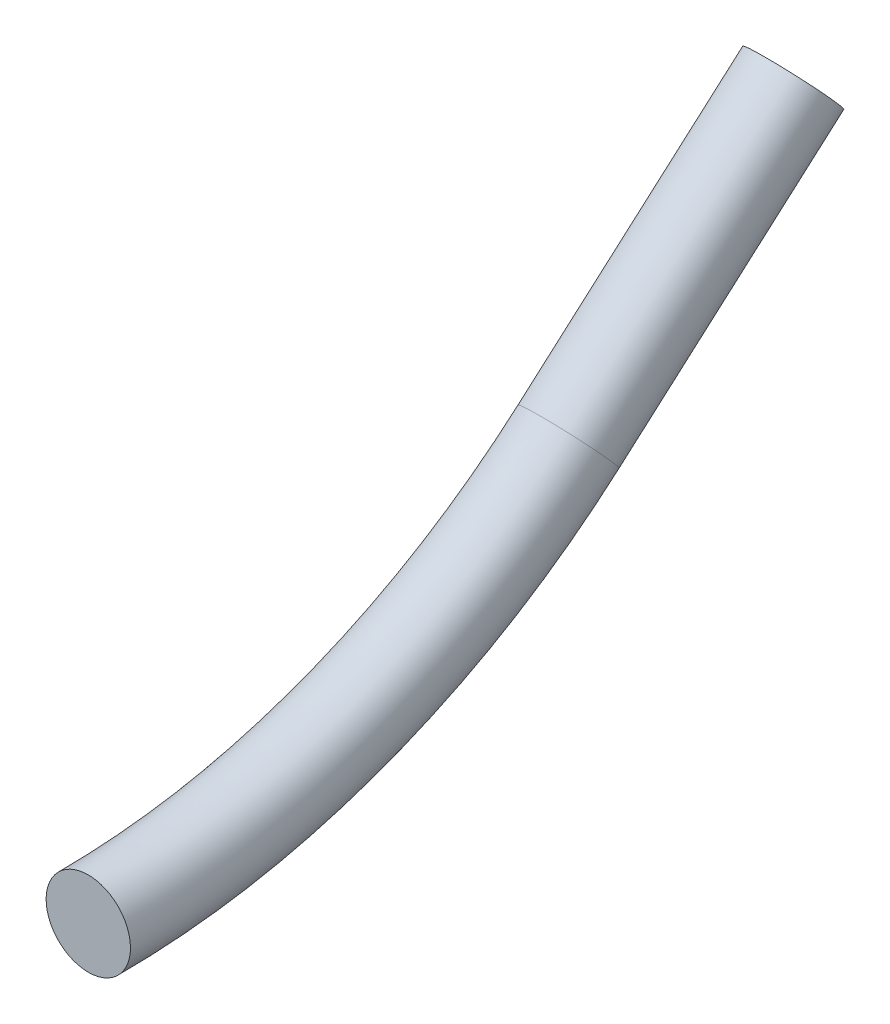
SolidWorks part; units mm, degrees
ref_plane "Front" through (0, 0, 0) normal (0, 0, 1) x (1, 0, 0)
ref_plane "Top" through (0, 0, 0) normal (0, 1, 0) x (1, 0, 0)
ref_plane "Right" through (0, 0, 0) normal (1, 0, 0) x (0, 0, -1)
sketch "Sketch1" plane through (0, 0, 0) normal (1, 0, 0) x (0, 0, -1)
  line L0 (-457.0208, -403.4156) -> (0, 0) construction
  line L1 (-457.0208, -403.4156) -> (-2130.5312, -1036.3679) construction
  line L2 (-1293.776, -719.8917) -> (-1235.9271, -872.8427) construction
  line L3 (-2130.5312, -1036.3679) -> (0, -1036.3679) construction
  line L4 (0, -1036.3679) -> (0, 0) construction
  line L5 (-298.7742, -263.7301) -> (-755.795, -667.1457)
  line L6 (-108.5313, -3087.971) -> (-11200.3387, -3250.5309) construction
  arc A0 (-2130.5312, -1036.3679) -> (-457.0208, -403.4156) centre (-2130.5312, 1492.4683) ccw construction
  arc A1 (-755.795, -667.1457) -> (-1732.0094, -1036.3679) centre (-1732.0094, 438.7865) cw
  dimension "D1" = 1828.8
  dimension "D4" = 609.6
  dimension "D5" = 1066.8
  dimension "D2" = 609.6
  dimension "D3" = 163.5252
  dimension "D6" = 0.84
ref_plane "Plane1" through (0, -263.7301, 298.7742) normal (0, -0.6618, 0.7497) x (1, 0, 0)
sketch "Sketch2" plane through (0, -263.7301, 298.7742) normal (0, -0.6618, 0.7497) x (1, 0, 0)
  circle A0 centre (0, 0) radius 85.725
  dimension "D1" = 171.45
sweep "Sweep1" add profiles "Sketch2" path "Sketch1"
ref_point "Point1"
